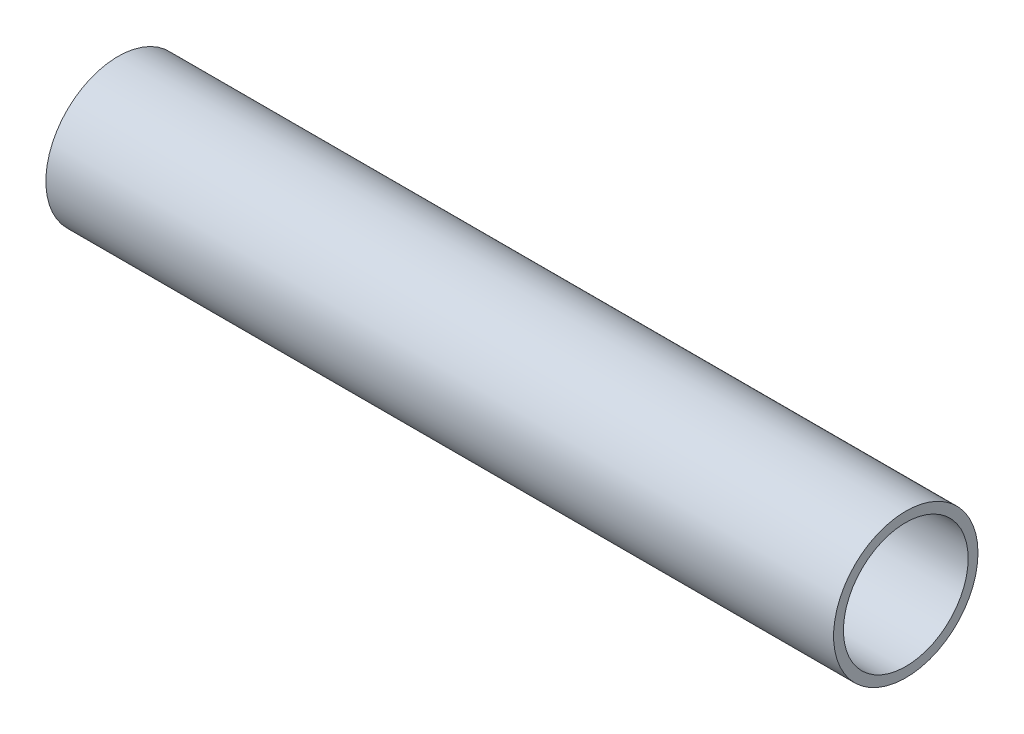
SolidWorks part; units mm, degrees
material "PVC 0.007 Plasticized"
ref_plane "Front Plane" through (0, 0, 0) normal (0, 0, 1) x (1, 0, 0)
ref_plane "Top Plane" through (0, 0, 0) normal (0, 1, 0) x (1, 0, 0)
ref_plane "Right Plane" through (0, 0, 0) normal (1, 0, 0) x (0, 0, -1)
sketch "Sketch1" plane through (0, 0, 0) normal (1, 0, 0) x (0, 0, -1)
  circle A0 centre (0, 0) radius 11
  circle A1 centre (0, 0) radius 9.5
  dimension "D1" = 1.5
extrude "Boss-Extrude1" add sketch "Sketch1" along normal blind 120
